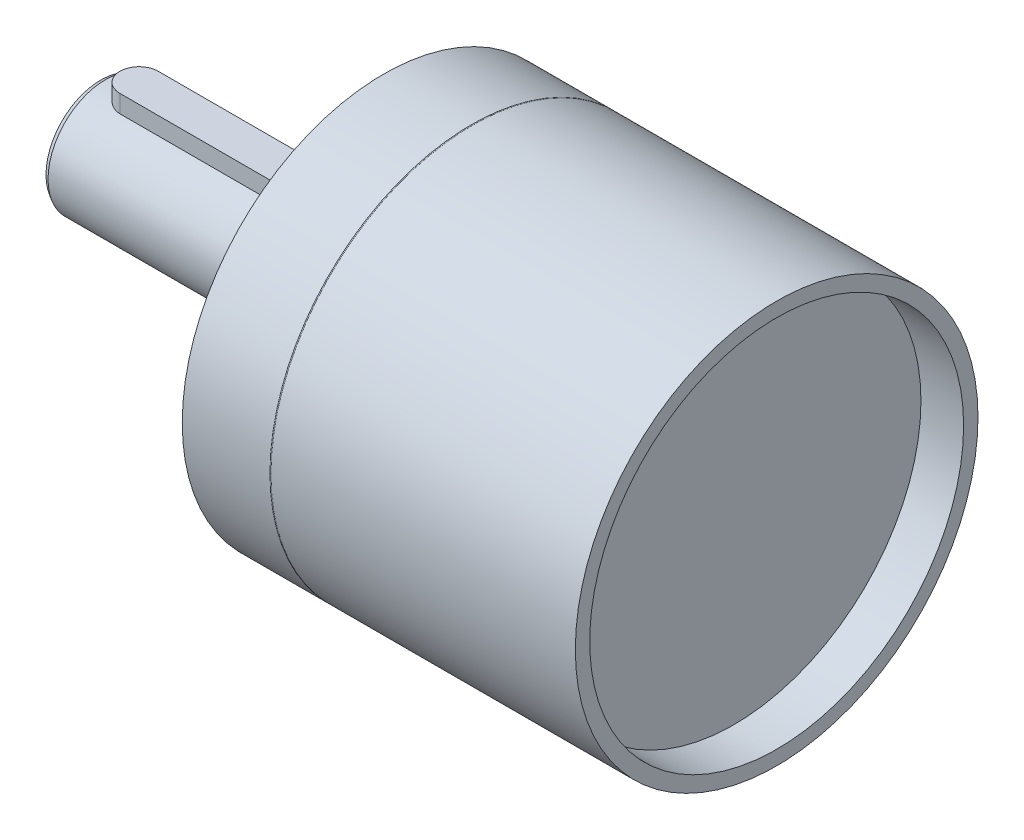
SolidWorks part; units mm, degrees
ref_plane "Front Plane" through (0, 0, 0) normal (0, 0, 1) x (1, 0, 0)
ref_plane "Top Plane" through (0, 0, 0) normal (0, 1, 0) x (1, 0, 0)
ref_plane "Right Plane" through (0, 0, 0) normal (1, 0, 0) x (0, 0, -1)
sketch "Sketch1" plane through (0, 0, 0) normal (0, 0, 1) x (1, 0, 0)
  line L0 (0, 21) -> (0, 0)
  line L1 (0, 0) -> (41, 0)
  line L2 (41, 0) -> (41, 21)
  line L3 (41, 21) -> (9.25, 21)
  line L4 (9.15, 21) -> (0, 21)
  line L5 (0, 0) -> (41, 0) construction
  arc A0 (9.25, 21) -> (9.15, 21) centre (9.2, 21.0866) cw
revolve "Revolve1" add sketch "Sketch1" angle 360 about L5
sketch "Sketch2" plane through (0, 0, 0) normal (-1, 0, 0) x (0, 0, 1)
  circle A0 centre (0, 0) radius 14
extrude "Boss-Extrude1" add sketch "Sketch2" along normal blind 3
sketch "Sketch3" plane through (-3, 0, 0) normal (-1, 0, 0) x (0, 0, 1)
  circle A0 centre (0, 0) radius 6
extrude "Boss-Extrude2" add sketch "Sketch3" along normal blind 26.5
ref_plane "Plane1" through (0, 7.5, 0) normal (0, 1, 0) x (1, 0, 0)
sketch "Sketch5" plane through (0, 7.5, 0) normal (0, 1, 0) x (1, 0, 0)
  line L0 (-9.5, 2) -> (-25.5, 2)
  line L1 (-25.5, -2) -> (-9.5, -2)
  arc A0 (-25.5, 2) -> (-25.5, -2) centre (-25.5, 0) ccw
  arc A1 (-9.5, -2) -> (-9.5, 2) centre (-9.5, 0) ccw
extrude "Boss-Extrude4" add sketch "Sketch5" against normal up to next
hole_wizard "M36 Clearance Hole1" positions "Sketch7" profile "Sketch6" hole size "M36" standard "ANSI Metric"
sketch "Sketch7" plane through (41, 0, 0) normal (1, 0, 0) x (0, 0, -1)
  point P0 (0, 0)
sketch "Sketch6" plane through (41, 0, 0) normal (0, 1, 0) x (0, 0, -1)
  line L0 (0, 0) -> (0, 4.45)
  line L1 (0, 4.45) -> (19.5, 4.45)
  line L2 (19.5, 4.45) -> (19.5, 0)
  line L5 (19.5, 0) -> (0, 0)
  line L10 (0, 4.45) -> (-19.5, 4.45) construction
  line L11 (0, -6.35) -> (0, 107.95) construction
  dimension "Hole Dia." = 39
  dimension "Hole Depth" = 4.45
  dimension "Drill Angle" = 180
hole_wizard "Ø1.5 (1.5) Diameter Hole1" positions "Sketch9" profile "Sketch8" hole size "Ø1.5" standard "ANSI Metric"
sketch "Sketch9" plane through (0, 0, 0) normal (-1, 0, 0) x (0, 0, 1)
  point P0 (-7.4623, 18.0157)
sketch "Sketch8" plane through (0, 18.0157, -7.4623) normal (0, 1, 0) x (0, 0, 1)
  line L0 (0, 0) -> (0, 2.4506)
  line L1 (0, 2.4506) -> (0.75, 2)
  line L2 (0.75, 2) -> (0.75, 0)
  line L5 (0.75, 0) -> (0, 0)
  line L10 (0, 2.4506) -> (-0.75, 2) construction
  line L11 (0, -6.35) -> (0, 107.95) construction
  dimension "Hole Dia." = 1.5
  dimension "Hole Depth" = 2
  dimension "Drill Angle" = 118
hole_wizard "Ø3.3 (3.3) Diameter Hole1" positions "Sketch11" profile "Sketch10" hole size "Ø3.3" standard "ANSI Metric"
sketch "Sketch11" plane through (0, 0, 0) normal (-1, 0, 0) x (0, 0, 1)
  point P0 (0, 17.5)
  point P1 (17.5, 0)
  point P2 (0, -17.5)
  point P3 (-17.5, 0)
sketch "Sketch10" plane through (0, 17.5, 0) normal (0, 1, 0) x (0, 0, 1)
  line L0 (0, 0) -> (0, 6.9914)
  line L1 (0, 6.9914) -> (1.65, 6)
  line L2 (1.65, 6) -> (1.65, 0)
  line L5 (1.65, 0) -> (0, 0)
  line L10 (0, 6.9914) -> (-1.65, 6) construction
  line L11 (0, -6.35) -> (0, 107.95) construction
  dimension "Hole Dia." = 3.3
  dimension "Hole Depth" = 6
  dimension "Drill Angle" = 118
hole_wizard "Ø1.25 (1.25) Diameter Hole1" positions "Sketch13" profile "Sketch12" hole size "Ø1.25" standard "ANSI Metric"
sketch "Sketch13" plane through (-29.5, 0, 0) normal (-1, 0, 0) x (0, 0, 1)
  point P0 (0, 0)
sketch "Sketch12" plane through (-29.5, 0, 0) normal (0, 1, 0) x (0, 0, 1)
  line L0 (0, 0) -> (0, 2.3)
  line L1 (0, 2.3) -> (0.625, 1.9392)
  line L2 (0.625, 1.9392) -> (0.625, 1.2124)
  line L3 (0.625, 1.2124) -> (1.325, 0)
  line L5 (1.325, 0) -> (0, 0)
  line L6 (-0.625, 1.2124) -> (-1.325, 0) construction
  line L10 (0, 2.3) -> (-0.625, 1.9392) construction
  line L11 (0, -6.35) -> (0, 107.95) construction
  dimension "Hole Dia." = 1.25
  dimension "Hole Depth" = 1.9392
  dimension "Near C'Sink Dia." = 2.65
  dimension "Near C'Sink Angle" = 60
  dimension "Drill Angle" = 120
chamfer "Chamfer1" distance 0.2887 angle 60 1 edges at (-29.5, 0, 6)
sketch "Sketch4" plane through (-3, 0, 0) normal (-1, 0, 0) x (0, 0, 1)
  line L0 (0.2939, -7.6168) -> (0.2939, -5.9928)
  line L1 (-0.2939, -5.9928) -> (-0.2939, -7.6168)
  arc A0 (0.2939, -5.9928) -> (-0.2939, -5.9928) centre (0, 0) ccw
  arc A1 (-0.2939, -7.6168) -> (-2.8825, -5.9928) centre (0.2939, -3.8048) cw
  arc A2 (-2.8825, -5.9928) -> (2.8825, -5.9928) centre (0, 0) cw
  arc A3 (2.8825, -5.9928) -> (0.2939, -7.6168) centre (0.2939, -4.7418) cw
extrude "Boss-Extrude3" [suppressed] add sketch "Sketch4" along normal blind 1
